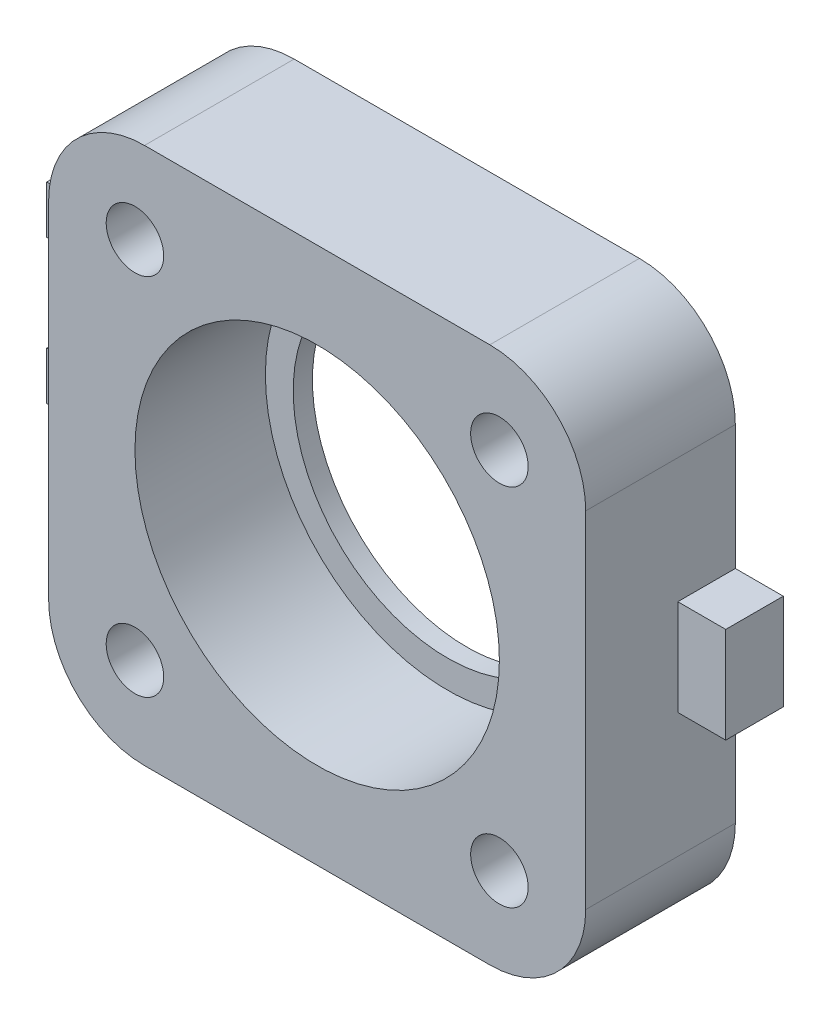
SolidWorks part; units mm, degrees
ref_plane "Alzado" through (0, 0, 0) normal (0, 0, 1) x (1, 0, 0)
ref_plane "Planta" through (0, 0, 0) normal (0, 1, 0) x (1, 0, 0)
ref_plane "Vista lateral" through (0, 0, 0) normal (1, 0, 0) x (0, 0, -1)
sketch "Croquis1" plane through (0, 0, 0) normal (0, 0, 1) x (1, 0, 0)
  line L1 (-14, -14) -> (14, -14)
  line L2 (-14, -14) -> (-14, 14)
  line L3 (-14, 14) -> (14, 14)
  line L4 (14, -14) -> (14, 14)
  line L5 (-14, -14) -> (14, 14) construction
  line L6 (-14, 14) -> (14, -14) construction
  circle A0 centre (0, 0) radius 8.05
  dimension "D1" = 16.1
  dimension "D2" = 28
  dimension "D3" = 28
extrude "Saliente-Extruir1" add sketch "Croquis1" along normal mid plane 1
sketch "Croquis2" plane through (0, 0, 0.5) normal (0, 0, 1) x (1, 0, 0)
  line L4 (14, -14) -> (14, 14)
  line L5 (14, 14) -> (-14, 14)
  line L6 (-14, 14) -> (-14, -14)
  line L7 (-14, -14) -> (14, -14)
  line L8 (14, -14) -> (14, 14)
  line L9 (14, 14) -> (-14, 14)
  line L10 (-14, 14) -> (-14, -14)
  line L11 (-14, -14) -> (14, -14)
  circle A0 centre (0, 0) radius 9.5
  dimension "D2" = 19
  dimension "D1" = 0
extrude "Saliente-Extruir2" add sketch "Croquis2" along normal blind 6.8
sketch "Croquis3" plane through (0, 0, 7.3) normal (0, 0, 1) x (1, 0, 0)
  line L0 (-9.5, 9.5) -> (9.5, 9.5) construction
  line L1 (9.5, 9.5) -> (9.5, -9.5) construction
  line L2 (9.5, -9.5) -> (-9.5, -9.5) construction
  line L3 (-9.5, -9.5) -> (-9.5, 9.5) construction
  line L5 (0, 13.0603) -> (0, -13.8489) construction
  line L6 (15.5492, 0) -> (-17.9148, 0) construction
  line L7 (11.03, 12.15) -> (7.97, 12.15)
  line L8 (-6.44, 9.5) -> (-7.97, 12.15)
  line L9 (-7.97, 12.15) -> (-11.03, 12.15)
  line L10 (-11.03, 12.15) -> (-12.56, 9.5)
  line L11 (-12.56, 9.5) -> (-11.03, 6.85)
  line L12 (-11.03, 6.85) -> (-7.97, 6.85)
  line L13 (-7.97, 6.85) -> (-6.44, 9.5)
  line L14 (7.97, 12.15) -> (6.44, 9.5)
  line L15 (6.44, 9.5) -> (7.97, 6.85)
  line L16 (7.97, 6.85) -> (11.03, 6.85)
  line L17 (11.03, 6.85) -> (12.56, 9.5)
  line L18 (12.56, 9.5) -> (11.03, 12.15)
  line L19 (-7.97, -6.85) -> (-11.03, -6.85)
  line L20 (-11.03, -6.85) -> (-12.56, -9.5)
  line L21 (-12.56, -9.5) -> (-11.03, -12.15)
  line L22 (-11.03, -12.15) -> (-7.97, -12.15)
  line L23 (-7.97, -12.15) -> (-6.44, -9.5)
  line L24 (-6.44, -9.5) -> (-7.97, -6.85)
  line L25 (11.03, -6.85) -> (7.97, -6.85)
  line L26 (7.97, -6.85) -> (6.44, -9.5)
  line L27 (6.44, -9.5) -> (7.97, -12.15)
  line L28 (7.97, -12.15) -> (11.03, -12.15)
  line L29 (11.03, -12.15) -> (12.56, -9.5)
  line L30 (12.56, -9.5) -> (11.03, -6.85)
  circle A0 centre (-9.5, 9.5) radius 1.5 construction
  circle A1 centre (-9.5, -9.5) radius 1.5 construction
  circle A2 centre (9.5, -9.5) radius 1.5 construction
  circle A3 centre (9.5, 9.5) radius 1.5 construction
  circle A4 centre (-9.5, 9.5) radius 2.65 construction
  circle A5 centre (9.5, 9.5) radius 2.65 construction
  circle A6 centre (-9.5, -9.5) radius 2.65 construction
  circle A7 centre (9.5, -9.5) radius 2.65 construction
  point P13 (0, -9.5)
  point P14 (-9.5, 0)
  dimension "D1" = 3
  dimension "D2" = 19
  dimension "D3" = 19
  dimension "D4" = 5.3
sketch "Croquis6" plane through (0, 0, -0.5) normal (0, 0, -1) x (-1, 0, 0)
  line L0 (-9.5, 9.5) -> (9.5, 9.5) construction
  line L1 (9.5, 9.5) -> (9.5, -9.5) construction
  line L2 (9.5, -9.5) -> (-9.5, -9.5) construction
  line L3 (-9.5, -9.5) -> (-9.5, 9.5) construction
  line L4 (0, 17.9373) -> (0, -16.6332) construction
  line L5 (16.9599, 0) -> (-18.6245, 0) construction
  circle A0 centre (-9.5, 9.5) radius 1.5
  circle A1 centre (9.5, 9.5) radius 1.5
  circle A2 centre (9.5, -9.5) radius 1.5
  circle A3 centre (-9.5, -9.5) radius 1.5
  point P13 (0, 9.5)
  point P14 (-9.5, 0)
  dimension "D1" = 3
  dimension "D2" = 19
  dimension "D3" = 19
sketch "Croquis7" plane through (0, 0, -0.5) normal (0, 0, -1) x (-1, 0, 0)
  line L0 (14, -14) -> (-14, -14) construction
  line L1 (-5, -14) -> (5, -14)
  line L2 (-5, -14) -> (-5, -18)
  line L3 (-5, -18) -> (5, -18)
  line L4 (5, -14) -> (5, -18)
  line L5 (-14, -14) -> (-14, 14) construction
  line L6 (-14, 2.5) -> (-16.5, 2.5)
  line L7 (-14, 2.5) -> (-14, -2.5)
  line L8 (-14, -2.5) -> (-16.5, -2.5)
  line L9 (-16.5, 2.5) -> (-16.5, -2.5)
  line L10 (14, 14) -> (14, -14) construction
  line L11 (14, 2.5) -> (16.5, 2.5)
  line L12 (14, 2.5) -> (14, -2.5)
  line L13 (14, -2.5) -> (16.5, -2.5)
  line L14 (16.5, 2.5) -> (16.5, -2.5)
  line L15 (0, 20.1506) -> (0, -30.1017) construction
  line L16 (-29.8997, 0) -> (35.1473, 0) construction
  line L17 (14, -5) -> (18.9, -5)
  line L18 (14, 2.5) -> (18.9, 2.5)
  line L19 (14, 2.5) -> (14, 5)
  line L20 (14, 5) -> (18.9, 5)
  line L21 (18.9, 2.5) -> (18.9, 5)
  line L22 (18.9, -2.5) -> (18.9, -5)
  line L23 (14, -2.5) -> (18.9, -2.5)
  line L24 (14, -2.5) -> (14, -5)
  point P23 (-16.5, 0)
  point P24 (16.5, 0)
  point P25 (0, -18)
  line M19 (-14, 14) -> (-14, -14)
  line M20 (-14, -14) -> (14, -14)
  line M21 (14, -14) -> (14, 14)
  dimension "D1" = 10
  dimension "D2" = 4
  dimension "D3" = 2.5
  dimension "D4" = 5
  dimension "D5" = 5
  dimension "D6" = 2.5
  dimension "D7" = 2.5
  dimension "D8" = 4.9
  dimension "D9" = 18
extrude "Saliente-Extruir3" add sketch "Croquis7" against normal blind 3 contours L6 L9 L8 M19 | L4 L2 L3 M20 | L23 L13 L17 L22 M21 | L14 L11 L13 M21 | L18 L21 L20 L11 M21
fillet "Redondeo1" radius 5 4 edges at (-14, -14, 3.4) (14, -14, 3.4) (14, 14, 3.4) (-14, 14, 3.4)
extrude "Cortar-Extruir3" cut sketch "Croquis6" against normal blind 10
